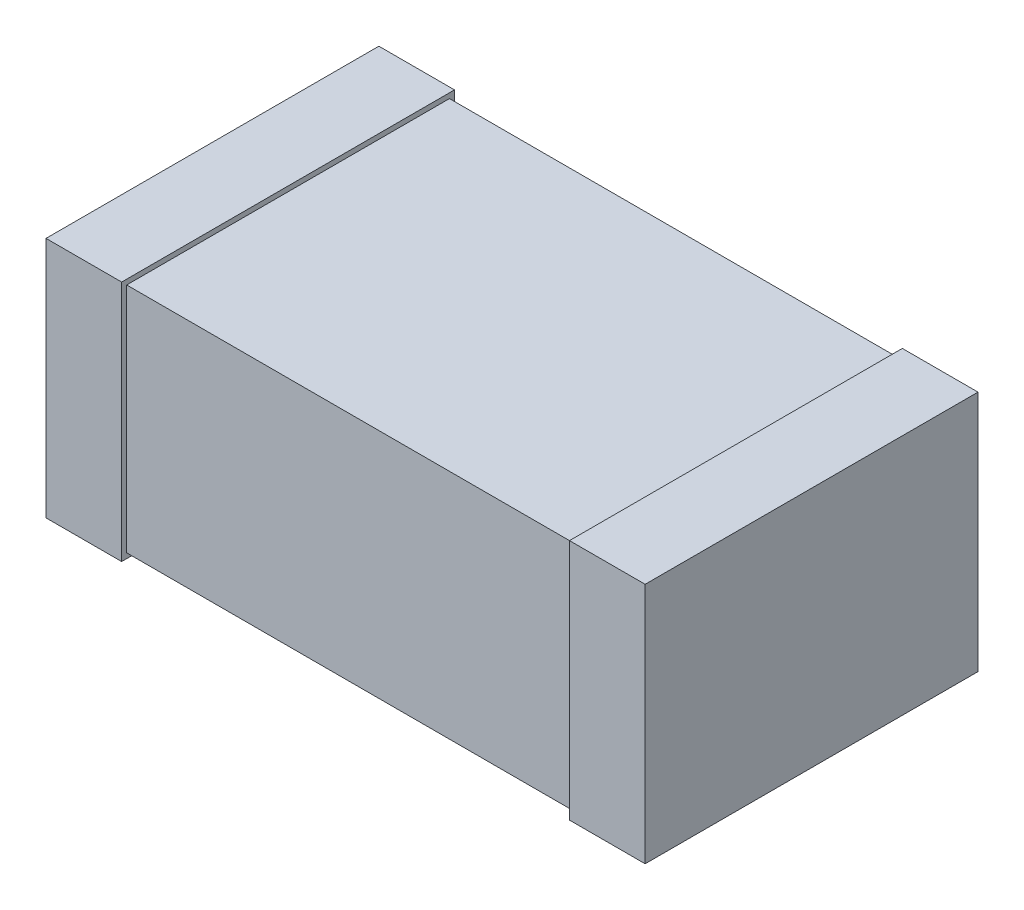
SolidWorks part; units mm, degrees
ref_plane "Front" through (0, 0, 0) normal (0, 0, 1) x (1, 0, 0)
ref_plane "Top" through (0, 0, 0) normal (0, 1, 0) x (1, 0, 0)
ref_plane "Right" through (0, 0, 0) normal (1, 0, 0) x (0, 0, -1)
sketch "Sketch1" plane through (0, 0, 0) normal (0, 1, 0) x (1, 0, 0)
  line L0 (-2.25, -1.6) -> (2.25, 1.6) construction
  line L1 (-2.25, 1.6) -> (2.25, 1.6)
  line L2 (-2.25, 1.6) -> (-2.25, -1.6)
  line L3 (-2.25, -1.6) -> (2.25, -1.6)
  line L4 (2.25, 1.6) -> (2.25, -1.6)
  dimension "D1" = 4.5
  dimension "D2" = 3.2
extrude "Boss-Extrude1" add sketch "Sketch1" along normal blind 2.3
sketch "Sketch2" plane through (2.25, 0, 0) normal (1, 0, 0) x (0, 0, -1)
  line L4 (-1.65, -0.05) -> (1.65, -0.05)
  line L5 (1.65, -0.05) -> (1.65, 2.35)
  line L6 (1.65, 2.35) -> (-1.65, 2.35)
  line L7 (-1.65, 2.35) -> (-1.65, -0.05)
  line L8 (-1.6, 0) -> (1.6, 0)
  line L9 (1.6, 0) -> (1.6, 2.3)
  line L10 (1.6, 2.3) -> (-1.6, 2.3)
  line L11 (-1.6, 2.3) -> (-1.6, 0)
  line L12 (-1.6, 0) -> (1.6, 0) construction
  line L13 (1.6, 0) -> (1.6, 2.3) construction
  line L14 (1.6, 2.3) -> (-1.6, 2.3) construction
  line L15 (-1.6, 2.3) -> (-1.6, 0) construction
  dimension "D1" = 0
  dimension "D2" = 0.05
extrude "Boss-Extrude2" add sketch "Sketch2" along normal blind 0.72 and the other way blind 0.03
mirror "Mirror1" about plane through (0, 0, 0) normal (1, 0, 0) of "Boss-Extrude2"
